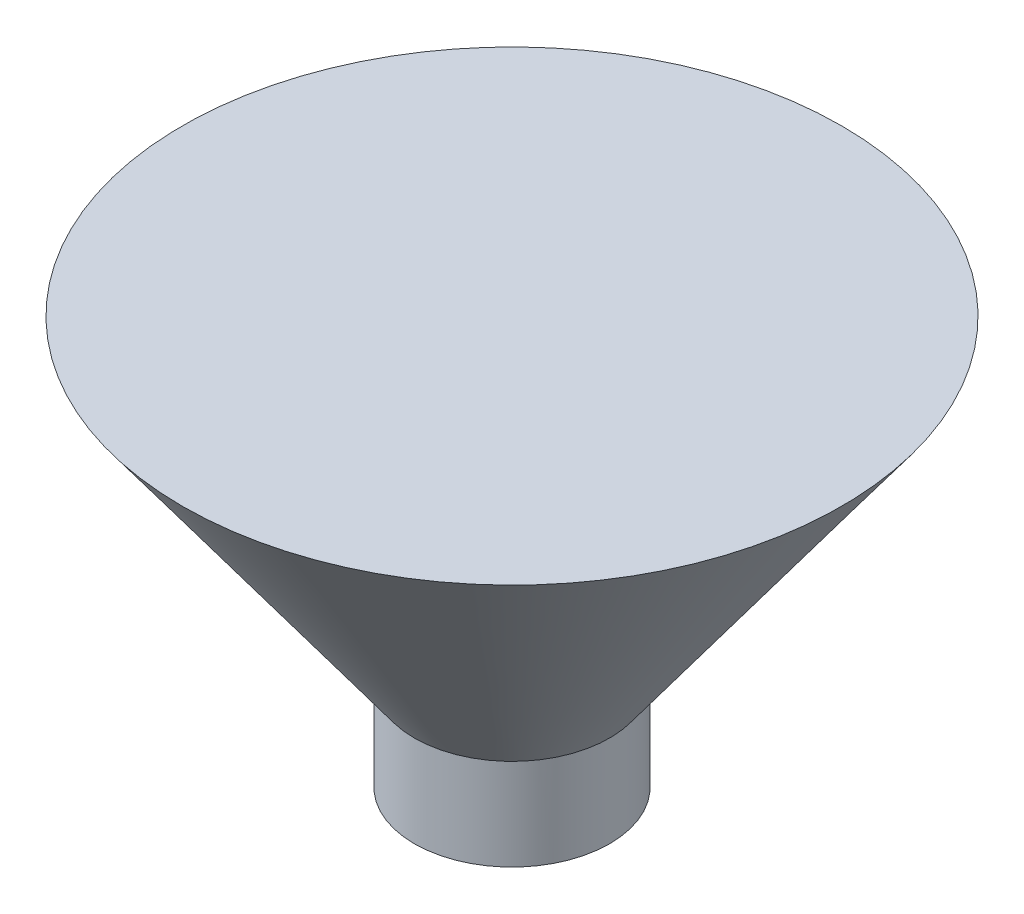
SolidWorks part; units mm, degrees
ref_plane "Front Plane" through (0, 0, 0) normal (0, 0, 1) x (1, 0, 0)
ref_plane "Top Plane" through (0, 0, 0) normal (0, 1, 0) x (1, 0, 0)
ref_plane "Right Plane" through (0, 0, 0) normal (1, 0, 0) x (0, 0, -1)
sketch "Sketch1" plane through (0, 0, 0) normal (0, 0, 1) x (1, 0, 0)
  line L0 (0, 0) -> (16, 0)
  line L1 (16, 0) -> (54, 51.8895)
  line L2 (54, 51.8895) -> (0, 51.8895)
  line L3 (0, 51.8895) -> (0, 0)
  line L4 (0, -12.4485) -> (0, 64.993) construction
revolve "Revolve1" add sketch "Sketch1" angle 360 about L4
sketch "Sketch2" plane through (0, 0, 0) normal (0, -1, 0) x (1, 0, 0)
  circle A0 centre (0, 0) radius 16
extrude "Boss-Extrude1" add sketch "Sketch2" along normal blind 15
